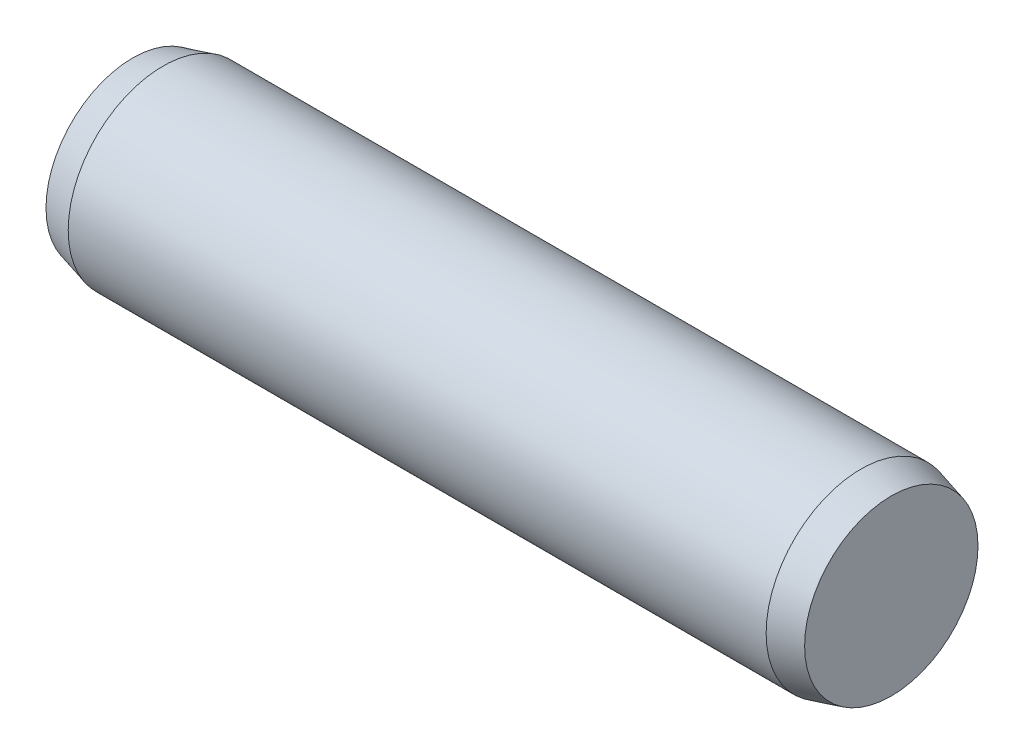
SolidWorks part; units mm, degrees
ref_plane "Plane1" through (0, 0, 0) normal (0, 0, 1) x (1, 0, 0)
ref_plane "Plane2" through (0, 0, 0) normal (0, 1, 0) x (1, 0, 0)
ref_plane "Plane3" through (0, 0, 0) normal (1, 0, 0) x (0, 0, -1)
sketch "Sketch1" plane through (0, 0, 0) normal (0, 0, 1) x (1, 0, 0)
  line L1 (-6.35, 0) -> (107.95, 0) construction
  line L2 (0, 0) -> (100, 0)
  line L3 (100, 0) -> (100, 11.4282)
  line L4 (100, 11.4282) -> (96, 12.5)
  line L5 (96, 12.5) -> (4, 12.5)
  line L6 (0, 11.4282) -> (0, 0)
  line L7 (0, 11.4282) -> (4, 12.5)
  dimension "Chamfer_len" = 4
  dimension "D3" = 15
  dimension "Diameter" = 25
  dimension "D1" = 4
  dimension "D2" = 15
  dimension "Length" = 100
revolve "Base-Revolve" add sketch "Sketch1" angle 360 about L1
equation "\"D3@Sketch1\" = 15.0"
equation "\"D1@Sketch1\" = \"Chamfer_len@Sketch1\""
equation "\"D2@Sketch1\" = \"D3@Sketch1\""
